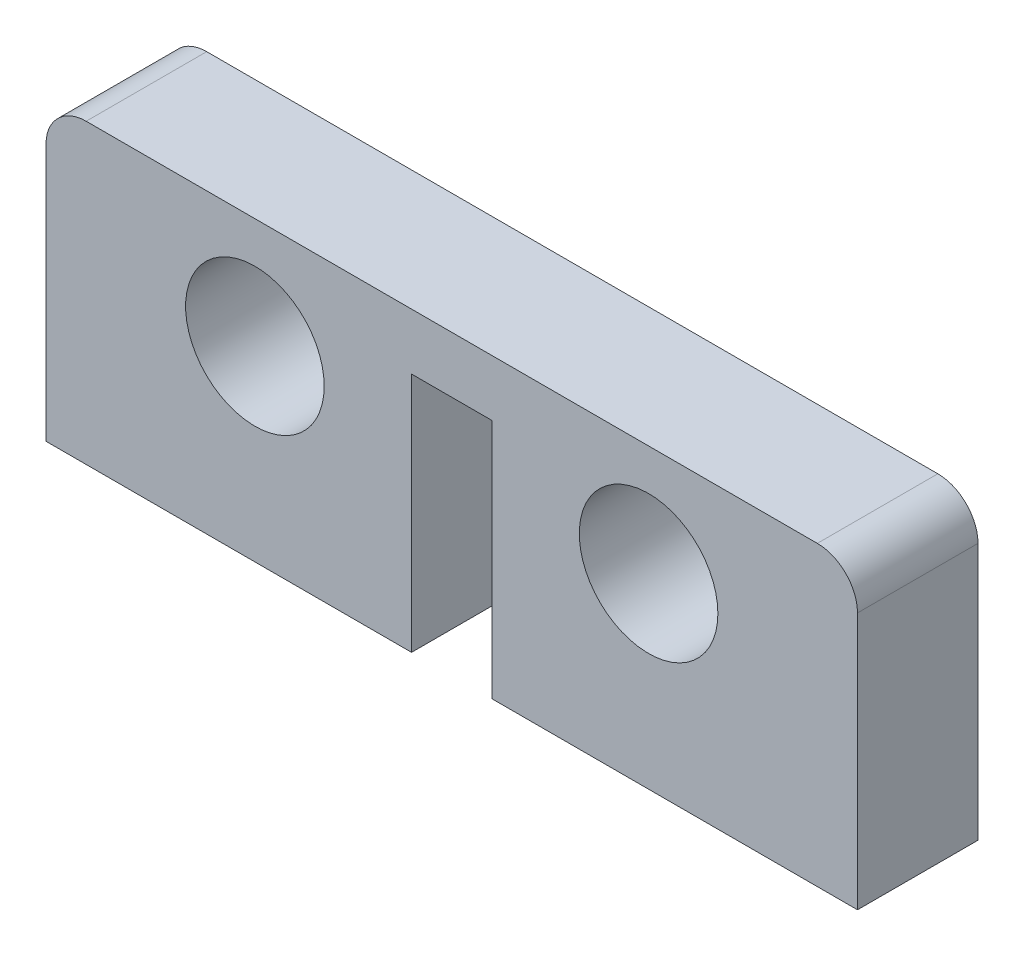
SolidWorks part; units mm, degrees
material "ABS"
ref_plane "Front Plane" through (0, 0, 0) normal (0, 0, 1) x (1, 0, 0)
ref_plane "Top Plane" through (0, 0, 0) normal (0, 1, 0) x (1, 0, 0)
ref_plane "Right Plane" through (0, 0, 0) normal (1, 0, 0) x (0, 0, -1)
sketch "Sketch1" plane through (0, 0, 0) normal (0, 0, 1) x (1, 0, 0)
  line L0 (0, 3.7) -> (0, -3.7) construction
  line L1 (-10.1, 3.7) -> (10.1, 3.7)
  line L2 (-10.1, 3.7) -> (-10.1, -3.7)
  line L3 (-10.1, -3.7) -> (10.1, -3.7)
  line L4 (10.1, 3.7) -> (10.1, -3.7)
  circle A0 centre (-4.9, 0.95) radius 1.725
  circle A1 centre (4.9, 0.95) radius 1.725
  dimension "D2" = 3.45
  dimension "D1" = 20.2
  dimension "D3" = 2.75
  dimension "D4" = 9.8
  dimension "D5" = 7.4
extrude "Boss-Extrude1" add sketch "Sketch1" along normal blind 3
sketch "Sketch2" plane through (0, 0, 3) normal (0, 0, 1) x (1, 0, 0)
  line L0 (-10.1, -3.7) -> (10.1, -3.7) construction
  line L1 (-1, -3.7) -> (1, -3.7)
  line L2 (-1, -3.7) -> (-1, 2.3)
  line L3 (-1, 2.3) -> (1, 2.3)
  line L4 (1, -3.7) -> (1, 2.3)
  line L5 (0, 2.3) -> (0, -3.7) construction
  dimension "D1" = 2
  dimension "D2" = 6
extrude "Cut-Extrude1" cut sketch "Sketch2" against normal blind 3
fillet "Fillet1" radius 1 2 edges at (10.1, 3.7, 1.5) (-10.1, 3.7, 1.5)
equation "\"D2@Sketch1\"=3.00mm+\"print_free@Parameters@Parameters.SLDPRT\""
